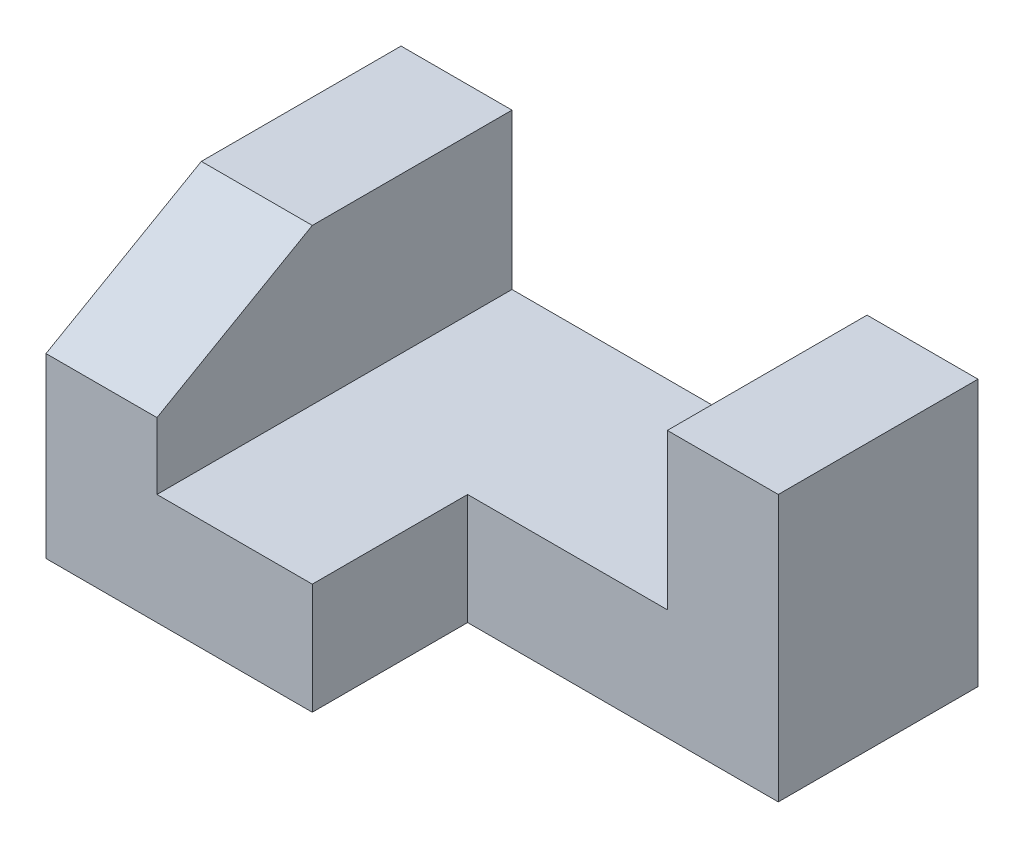
SolidWorks part; units mm, degrees
ref_plane "정면" through (0, 0, 0) normal (0, 0, 1) x (1, 0, 0)
ref_plane "윗면" through (0, 0, 0) normal (0, 1, 0) x (1, 0, 0)
ref_plane "우측면" through (0, 0, 0) normal (1, 0, 0) x (0, 0, -1)
sketch "Sketch1" plane through (0, 0, 0) normal (0, 1, 0) x (1, 0, 0)
  line L1 (0, 0) -> (60, 0)
  line L2 (0, 0) -> (0, 80)
  line L3 (0, 80) -> (130, 80)
  line L4 (130, 35) -> (130, 80)
  line L7 (130, 35) -> (60, 35)
  line L8 (60, 0) -> (60, 35)
  point P8 (0, 0)
  point P9 (0, 0)
  dimension "D1" = 130
  dimension "D2" = 80
  dimension "D3" = 60
  dimension "D4" = 45
extrude "Boss-Extrude1" add sketch "Sketch1" along normal blind 25 contours L1 L8 L7 L4 L3 L2
sketch "Sketch2" plane through (0, 0, 0) normal (-1, 0, 0) x (0, 0, 1)
  line L0 (-35, 60) -> (0, 60)
  line L1 (-80, 25) -> (0, 25)
  line L2 (-80, 25) -> (-80, 60)
  line L3 (-80, 60) -> (0, 60)
  line L4 (0, 25) -> (0, 60)
  line L5 (0, 40) -> (-35, 60)
  line L6 (0, 0) -> (-80, 0) construction
  line M7 (0, 25) -> (-80, 25)
  dimension "D1" = 35
  dimension "D2" = 40
  dimension "D3" = 45
extrude "Boss-Extrude2" add sketch "Sketch2" against normal blind 25 contours L4 L5 L3 L2 M7
sketch "Sketch3" plane through (130, 0, 0) normal (1, 0, 0) x (0, 0, -1)
  line L0 (80, 25) -> (80, 60) construction
  line L1 (35, 25) -> (80, 25)
  line L2 (35, 25) -> (35, 60)
  line L3 (35, 60) -> (80, 60)
  line L4 (80, 25) -> (80, 60)
  line L5 (35, 0) -> (80, 0) construction
  dimension "D1" = 60
extrude "Boss-Extrude3" add sketch "Sketch3" against normal blind 25
